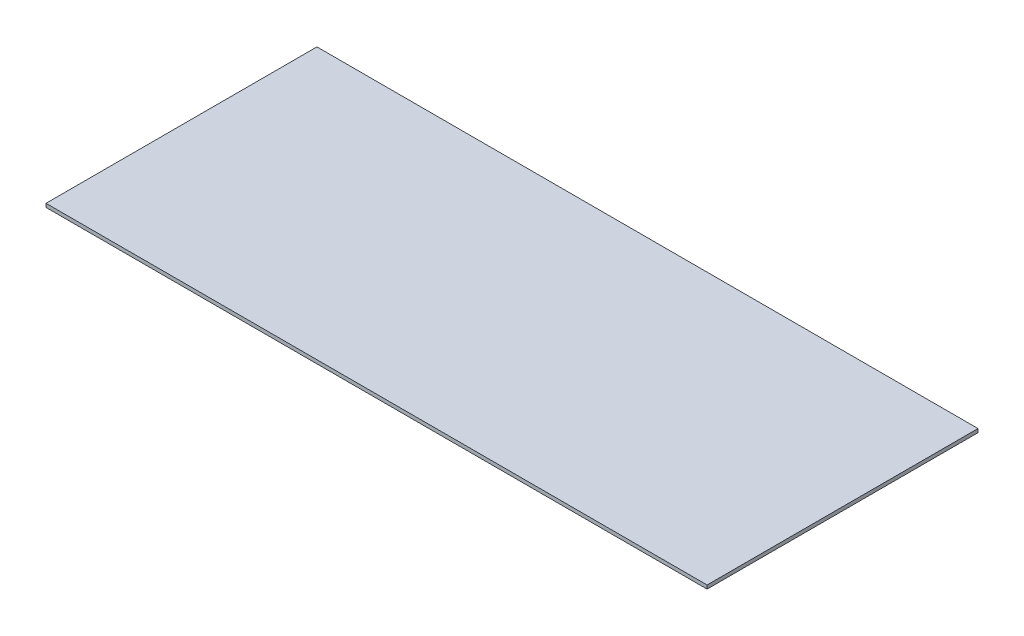
SolidWorks part; units mm, degrees
ref_plane "Front Plane" through (0, 0, 0) normal (0, 0, 1) x (1, 0, 0)
ref_plane "Top Plane" through (0, 0, 0) normal (0, 1, 0) x (1, 0, 0)
ref_plane "Right Plane" through (0, 0, 0) normal (1, 0, 0) x (0, 0, -1)
sketch "Sketch1" plane through (0, 0, 0) normal (0, 1, 0) x (1, 0, 0)
  line L1 (183, 75) -> (-183, 75)
  line L2 (183, 75) -> (183, -75)
  line L3 (183, -75) -> (-183, -75)
  line L4 (-183, 75) -> (-183, -75)
  line L5 (183, 75) -> (-183, -75) construction
  line L6 (183, -75) -> (-183, 75) construction
  point P0 (0, 0)
  dimension "D1" = 366
  dimension "D2" = 150
extrude "Boss-Extrude1" add sketch "Sketch1" along normal blind 2
